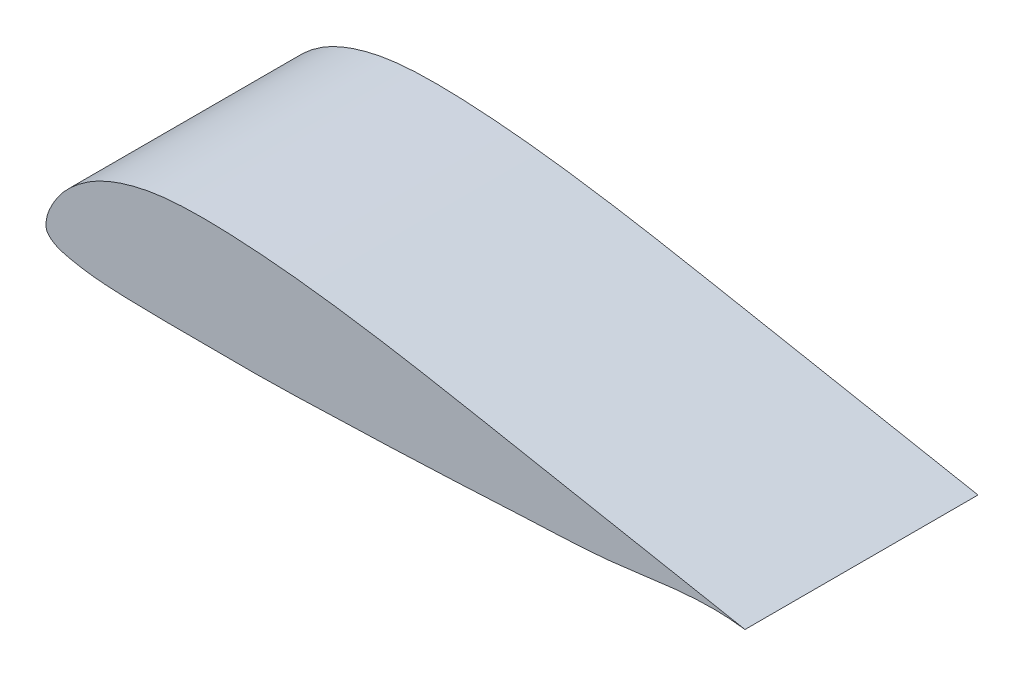
SolidWorks part; units mm, degrees
ref_plane "Front Plane" through (0, 0, 0) normal (0, 0, 1) x (1, 0, 0)
ref_plane "Top Plane" through (0, 0, 0) normal (0, 1, 0) x (1, 0, 0)
ref_plane "Right Plane" through (0, 0, 0) normal (1, 0, 0) x (0, 0, -1)
sketch "Sketch1" plane through (0, 0, 0) normal (0, 0, 1) x (1, 0, 0)
  line L0 (0, 0) -> (0, 252.7344) construction
  line L1 (0, 0) -> (300, 0) construction
  line L2 (1.5, 6.9) -> (1.5, -3.18) construction
  line L3 (3, 9.9) -> (3, -4.35) construction
  line L4 (6, 14.52) -> (6, -5.85) construction
  line L5 (9, 18) -> (9, -6.69) construction
  line L6 (15, 23.25) -> (15, -7.89) construction
  line L7 (21, 27.15) -> (21, -8.7) construction
  line L8 (30, 31.2) -> (30, -9.36) construction
  line L9 (45, 35.1) -> (45, -9.76) construction
  line L10 (60, 36.54) -> (60, -9.93) construction
  line L11 (75, 36.54) -> (75, -9.96) construction
  line L12 (90, 35.76) -> (90, -9.98) construction
  line L13 (120, 32.7) -> (120, -9.24) construction
  line L14 (150, 28.2) -> (150, -8.22) construction
  line L15 (180, 22.8) -> (180, -6.9) construction
  line L16 (210, 17.1) -> (210, -5.4) construction
  line L17 (240, 11.4) -> (240, -3.66) construction
  line L18 (270, 5.7) -> (270, 0) construction
  spline S0 degree 3 poles (0, 0) (-0.0616, 3.6359) (2.0231, 8.5716) (5.7169, 14.3517) (9.6846, 18.9071) (14.6817, 23.2224) (21.6783, 27.7929) (31.658, 32.1515) (44.7961, 35.4946) (59.9739, 36.7677) (75.011, 36.6564) (95.0451, 35.5728) (120.0914, 32.9228) (150.0744, 28.3437) (180.0252, 22.8335) (209.9981, 17.0902) (250.0013, 9.5066) (279.9994, 3.7967) (300, 0) knots 0 0 0 0 0.032627 0.049883 0.064276 0.089251 0.111668 0.142584 0.191136 0.23834 0.285329 0.332382 0.426847 0.521876 0.617364 0.713023 0.808682 1 1 1 1
  spline S1 degree 3 poles (0, 0) (0.11, -2.0883) (2.3189, -4.1474) (5.8853, -5.9363) (9.9735, -6.9459) (14.966, -7.9536) (21.9774, -8.8831) (31.9884, -9.5478) (44.9989, -9.7693) (59.9994, -9.9689) (74.9999, -9.9352) (95.004, -10.089) (120.0037, -9.2232) (150.0054, -8.2843) (180.0074, -6.9583) (209.9927, -5.2812) (250.1174, -3.9923) (279.7303, 2.8907) (300, 0) knots 0 0 0 0 0.017855 0.028908 0.039175 0.059338 0.07929 0.109028 0.158476 0.207909 0.25734 0.30677 0.405661 0.504578 0.603535 0.702519 0.801546 1 1 1 1
  dimension "D1" = 300
  dimension "D2" = 1.5
  dimension "D3" = 6.9
  dimension "D4" = 3.18
  dimension "D5" = 3
  dimension "D6" = 9.9
  dimension "D7" = 4.35
  dimension "D8" = 6
  dimension "D9" = 14.52
  dimension "D10" = 5.85
  dimension "D11" = 9
  dimension "D12" = 18
  dimension "D13" = 6.69
  dimension "D14" = 15
  dimension "D15" = 7.89
  dimension "D16" = 23.25
  dimension "D17" = 27.15
  dimension "D18" = 8.7
  dimension "D19" = 21
  dimension "D20" = 30
  dimension "D21" = 31.2
  dimension "D22" = 9.36
  dimension "D23" = 45
  dimension "D24" = 35.1
  dimension "D25" = 9.76
  dimension "D26" = 60
  dimension "D27" = 36.54
  dimension "D28" = 9.93
  dimension "D29" = 75
  dimension "D30" = 36.54
  dimension "D31" = 9.96
  dimension "D32" = 90
  dimension "D33" = 35.76
  dimension "D34" = 9.98
  dimension "D35" = 120
  dimension "D36" = 32.7
  dimension "D37" = 9.24
  dimension "D38" = 150
  dimension "D39" = 28.2
  dimension "D40" = 8.22
  dimension "D41" = 180
  dimension "D42" = 6.9
  dimension "D43" = 22.8
  dimension "D44" = 210
  dimension "D45" = 17.1
  dimension "D46" = 5.4
  dimension "D47" = 240
  dimension "D48" = 11.4
  dimension "D49" = 3.66
  dimension "D50" = 270
  dimension "D51" = 5.7
  dimension "D52" = 0
extrude "Boss-Extrude1" add sketch "Sketch1" along normal blind 100
